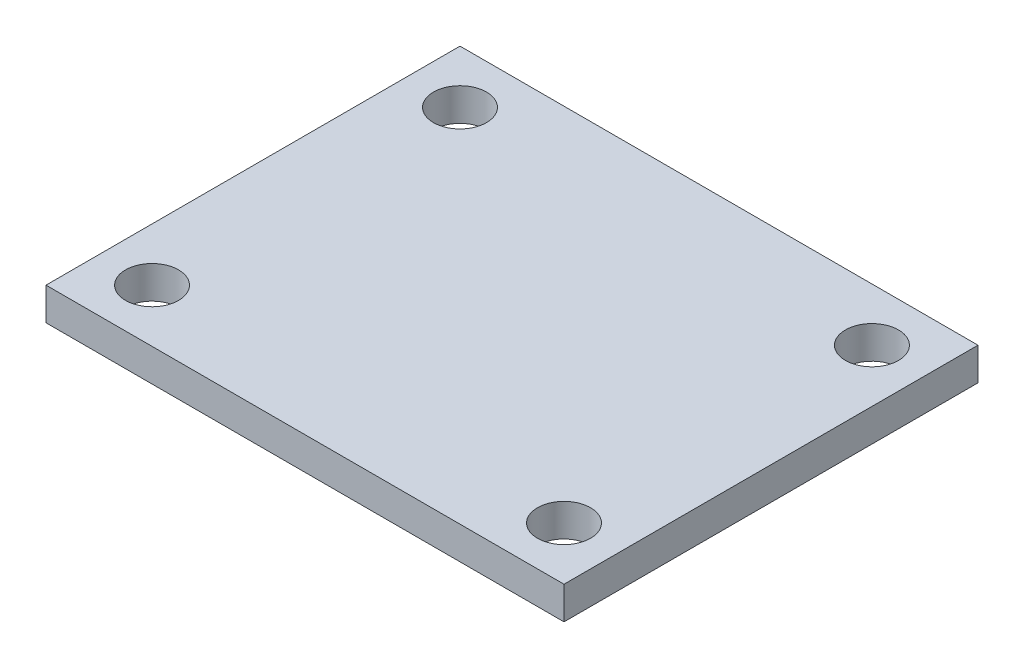
SolidWorks part; units mm, degrees
ref_plane "Front" through (0, 0, 0) normal (0, 0, 1) x (1, 0, 0)
ref_plane "Top" through (0, 0, 0) normal (0, 1, 0) x (1, 0, 0)
ref_plane "Right" through (0, 0, 0) normal (1, 0, 0) x (0, 0, -1)
sketch "Эскиз1" plane through (0, 0, 0) normal (0, 1, 0) x (1, 0, 0)
  line L1 (-12.7, 10.15) -> (12.7, 10.15)
  line L2 (-12.7, 10.15) -> (-12.7, -10.15)
  line L3 (-12.7, -10.15) -> (12.7, -10.15)
  line L4 (12.7, 10.15) -> (12.7, -10.15)
  line L5 (-12.7, 10.15) -> (12.7, -10.15) construction
  line L6 (-12.7, -10.15) -> (12.7, 10.15) construction
  point P0 (0, 0)
  dimension "D1" = 20.3
  dimension "D2" = 25.4
extrude "Бобышка-Вытянуть1" add sketch "Эскиз1" along normal blind 1.6
sketch "Эскиз2" plane through (0, 1.6, 0) normal (0, 1, 0) x (1, 0, 0)
  line L0 (166.6667, 500) -> (833.3333, 500) construction
  line L1 (143.4294, 469.8772) -> (810.096, 469.8772) construction
sketch "Эскиз3" plane through (0, 1.6, 0) normal (0, 1, 0) x (1, 0, 0)
  line L1 (12.7, 10.15) -> (-12.7, 10.15) construction
  line L2 (-12.7, 10.15) -> (-12.7, -10.15) construction
  line L3 (0, 0) -> (0, 11.5576) construction
  line L4 (0, 0) -> (8.0585, 0) construction
  circle A0 centre (-10.1, 7.55) radius 1.3
  circle A1 centre (10.1, 7.55) radius 1.3
  circle A2 centre (10.1, -7.55) radius 1.3
  circle A3 centre (-10.1, -7.55) radius 1.3
  dimension "D1" = 2.6
  dimension "D2" = 2.6
  dimension "D3" = 2.6
extrude "Вырез-Вытянуть1" cut sketch "Эскиз3" against normal blind 1.6
